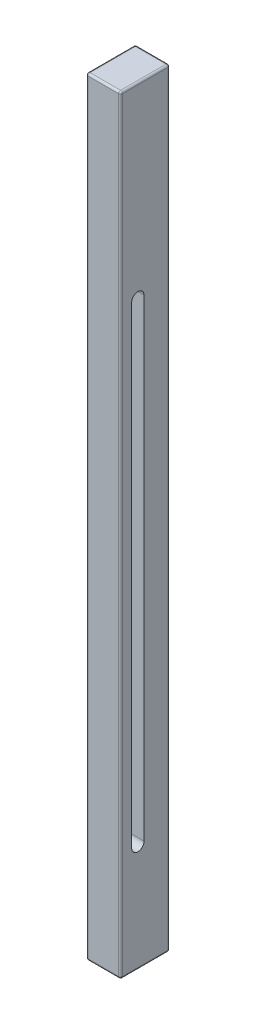
SolidWorks part; units mm, degrees
material "Pine"
ref_plane "Front Plane" through (0, 0, 0) normal (0, 0, 1) x (1, 0, 0)
ref_plane "Top Plane" through (0, 0, 0) normal (0, 1, 0) x (1, 0, 0)
ref_plane "Right Plane" through (0, 0, 0) normal (1, 0, 0) x (0, 0, -1)
sketch "Sketch1" plane through (0, 0, 0) normal (0, 1, 0) x (1, 0, 0)
  line L1 (22.225, -31.75) -> (-22.225, -31.75)
  line L2 (22.225, -31.75) -> (22.225, 31.75)
  line L3 (22.225, 31.75) -> (-22.225, 31.75)
  line L4 (-22.225, -31.75) -> (-22.225, 31.75)
  line L5 (22.225, -31.75) -> (-22.225, 31.75) construction
  line L6 (22.225, 31.75) -> (-22.225, -31.75) construction
  point P0 (0, 0)
  dimension "D1" = 44.45
  dimension "D2" = 63.5
extrude "Boss-Extrude1" add sketch "Sketch1" along normal blind 990.6
fillet "Fillet1" radius 2.54 4 edges at (-22.225, 495.3, -31.75) (-22.225, 495.3, 31.75) (22.225, 495.3, -31.75) (22.225, 495.3, 31.75)
sketch "Sketch2" plane through (22.225, 0, 0) normal (1, 0, 0) x (0, 0, -1)
  line L0 (-9.525, 749.3) -> (-9.525, 139.7) construction
  line L1 (-1.5875, 749.3) -> (-1.5875, 139.7)
  line L2 (-17.4625, 749.3) -> (-17.4625, 139.7)
  line L3 (-29.21, 990.6) -> (29.21, 990.6) construction
  line L5 (-31.75, 0) -> (-31.75, 990.6) construction
  arc A0 (-1.5875, 749.3) -> (-17.4625, 749.3) centre (-9.525, 749.3) ccw
  arc A1 (-17.4625, 139.7) -> (-1.5875, 139.7) centre (-9.525, 139.7) ccw
  point P3 (-9.525, 444.5)
  dimension "D1" = 609.6
  dimension "D2" = 15.875
  dimension "D3" = 241.3
  dimension "D4" = 14.2875
extrude "Cut-Extrude1" cut sketch "Sketch2" against normal blind 23.495
fillet "Fillet2" radius 2.54 16 edges at (21.4811, 990.6, -31.0061) (22.225, 990.6, 0) (21.4811, 990.6, 31.0061) (0, 990.6, 31.75) (-21.4811, 990.6, 31.0061) (-22.225, 990.6, 0) (-21.4811, 990.6, -31.0061) (0, 990.6, -31.75) (-21.4811, 0, 31.0061) (0, 0, 31.75) (21.4811, 0, 31.0061) (22.225, 0, 0) (21.4811, 0, -31.0061) (0, 0, -31.75) (-21.4811, 0, -31.0061) (-22.225, 0, 0)
sketch "Sketch3" plane through (0, 0, 0) normal (0, -1, 0) x (1, 0, 0)
  circle A0 centre (0, 0) radius 9.525
  dimension "D1" = 19.05
extrude "Cut-Extrude2" cut sketch "Sketch3" against normal blind 25.4
sketch "Sketch4" plane through (0, 0, -31.75) normal (0, 0, -1) x (-1, 0, 0)
  line L0 (0, 914.4) -> (0, 863.6) construction
  line L1 (6.35, 914.4) -> (6.35, 863.6)
  line L2 (-6.35, 914.4) -> (-6.35, 863.6)
  line L3 (0, 666.75) -> (0, 615.95) construction
  line L4 (6.35, 666.75) -> (6.35, 615.95)
  line L5 (-6.35, 666.75) -> (-6.35, 615.95)
  line L6 (0, 342.9) -> (0, 292.1) construction
  line L7 (6.35, 342.9) -> (6.35, 292.1)
  line L8 (-6.35, 342.9) -> (-6.35, 292.1)
  line L10 (-19.685, 990.6) -> (19.685, 990.6) construction
  arc A0 (6.35, 914.4) -> (-6.35, 914.4) centre (0, 914.4) ccw
  arc A1 (-6.35, 863.6) -> (6.35, 863.6) centre (0, 863.6) ccw
  arc A2 (6.35, 666.75) -> (-6.35, 666.75) centre (0, 666.75) ccw
  arc A3 (-6.35, 615.95) -> (6.35, 615.95) centre (0, 615.95) ccw
  arc A4 (6.35, 342.9) -> (-6.35, 342.9) centre (0, 342.9) ccw
  arc A5 (-6.35, 292.1) -> (6.35, 292.1) centre (0, 292.1) ccw
  point P2 (0, 889)
  point P9 (0, 641.35)
  point P16 (0, 317.5)
  dimension "D1" = 101.6
  dimension "D2" = 349.25
  dimension "D3" = 673.1
  dimension "D4" = 12.7
  dimension "D5" = 50.8
  dimension "D6" = 50.8
  dimension "D7" = 12.7
  dimension "D8" = 12.7
  dimension "D9" = 50.8
extrude "Cut-Extrude3" cut sketch "Sketch4" against normal blind 25.4
